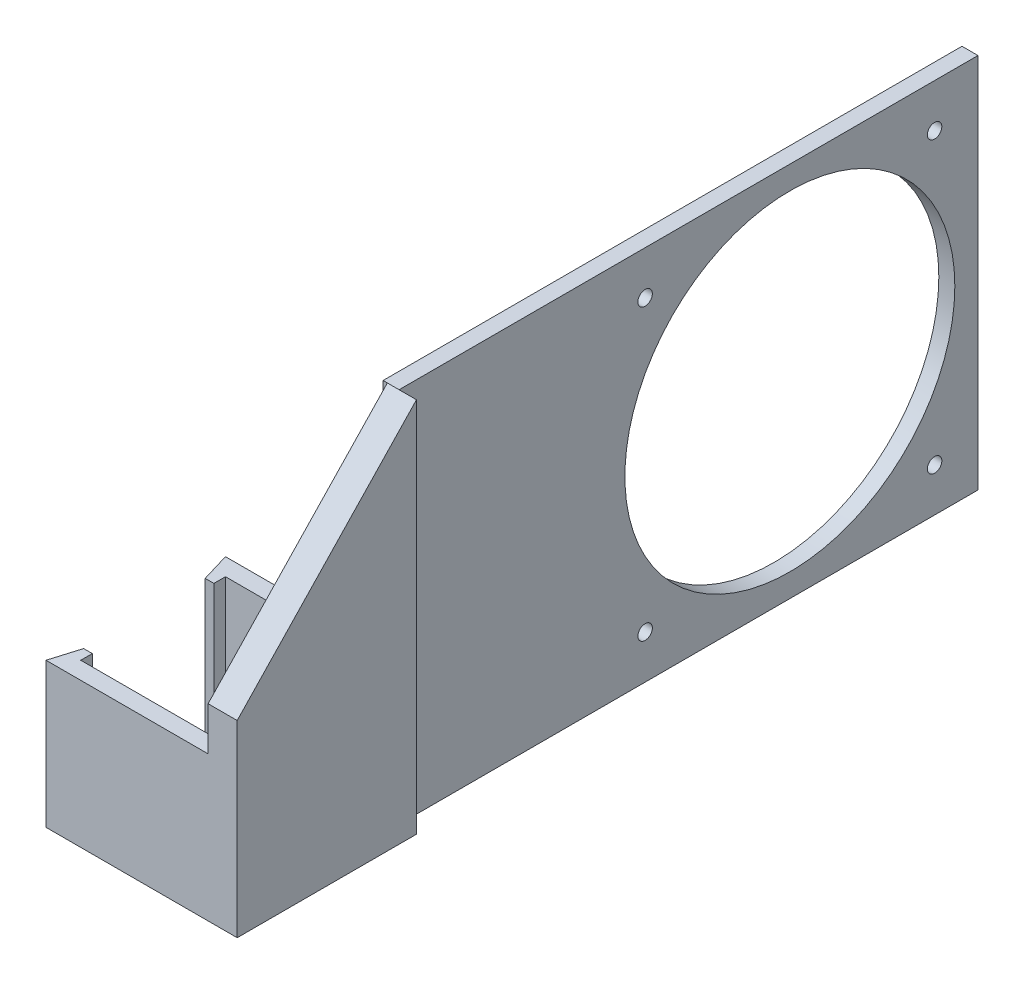
SolidWorks part; units mm, degrees
ref_plane "Спереди" through (0, 0, 0) normal (0, 0, 1) x (1, 0, 0)
ref_plane "Сверху" through (0, 0, 0) normal (0, 1, 0) x (1, 0, 0)
ref_plane "Справа" through (0, 0, 0) normal (1, 0, 0) x (0, 0, -1)
sketch "Эскиз1" plane through (0, 0, 0) normal (0, 1, 0) x (1, 0, 0)
  line L0 (-66.8258, 34.9697) -> (-66.8258, 29.9697)
  line L1 (-63.8258, 29.9697) -> (-63.8258, 31.9697)
  line L2 (-63.8258, 31.9697) -> (-38.8258, 31.9697)
  line L3 (-38.8258, 31.9697) -> (-38.8258, 6.9697)
  line L4 (-38.8258, 6.9697) -> (-63.8258, 6.9697)
  line L5 (-63.8258, 6.9697) -> (-63.8258, 8.9697)
  line L6 (-63.8258, 8.9697) -> (-66.8258, 8.9697)
  line L7 (-66.8258, 8.9697) -> (-66.8258, 3.9697)
  line L8 (-66.8258, 3.9697) -> (-22.1235, 3.9697)
  line L9 (-22.1235, 3.9697) -> (-36.579, 34.9697)
  line L10 (-36.579, 34.9697) -> (-66.8258, 34.9697)
  line L11 (-66.8258, 29.9697) -> (-63.8258, 29.9697)
  dimension "D1" = 25
  dimension "D2" = 25
  dimension "D3" = 25
  dimension "D4" = 155
  dimension "D5" = 3
  dimension "D6" = 3
  dimension "D7" = 3
  dimension "D8" = 3
  dimension "D9" = 2
  dimension "D10" = 2
extrude "Бобышка-Вытянуть1" add sketch "Эскиз1" along normal blind 25
sketch "Эскиз3" plane through (0, 0, 0) normal (0, -1, 0) x (1, 0, 0)
  line L0 (-66.8258, -3.9697) -> (-65.3258, -8.9697)
  line L1 (-63.8258, -8.9697) -> (-66.8258, -8.9697) construction
  line L2 (-65.3258, -8.9697) -> (-66.8258, -8.9697)
  line L3 (-66.8258, -8.9697) -> (-66.8258, -3.9697)
  line L4 (-66.8258, -29.9697) -> (-66.8258, -34.9697)
  line L5 (-66.8258, -34.9697) -> (-65.3258, -29.9697)
  line L6 (-66.8258, -29.9697) -> (-63.8258, -29.9697) construction
  line L7 (-65.3258, -29.9697) -> (-66.8258, -29.9697)
extrude "Вырез-Вытянуть4" cut sketch "Эскиз3" against normal through all
sketch "Эскиз7" plane through (0, 0, 0) normal (0, -1, 0) x (-1, 0, 0)
  line L1 (36.0076, 1.3029) -> (19.3993, 1.3029)
  line L2 (36.0076, 1.3029) -> (36.0076, 39.7765)
  line L3 (36.0076, 39.7765) -> (19.3993, 39.7765)
  line L4 (19.3993, 1.3029) -> (19.3993, 39.7765)
extrude "Вырез-Вытянуть14" cut sketch "Эскиз7" against normal through all
sketch "Эскиз8" plane through (0, 0, 0) normal (0, -1, 0) x (-1, 0, 0)
  line L0 (66.8258, 3.9697) -> (36.0076, 3.9697) construction
  line L1 (38.7989, 3.9697) -> (33.7989, 3.9697)
  line L2 (38.7989, 3.9697) -> (38.7989, 34.9383)
  line L3 (38.7989, 34.9383) -> (33.7989, 34.9383)
  line L4 (33.7989, 3.9697) -> (33.7989, 34.9383)
  dimension "D1" = 5
extrude "Бобышка-Вытянуть2" add sketch "Эскиз8" against normal up to surface (25 mm away) up to face at (-54.2963, 25, -20.5678)
sketch "Эскиз9" plane through (0, 0, -34.9383) normal (0, 0, -1) x (-1, 0, 0)
  line L0 (36.5643, 0) -> (33.7989, 0) construction
  line L1 (36.7989, 0) -> (39.5643, 0)
  line L2 (36.7989, 0) -> (36.7989, 65)
  line L3 (36.7989, 65) -> (39.5643, 65)
  line L4 (39.5643, 0) -> (39.5643, 65)
  line L5 (33.7989, 25) -> (33.7989, 0) construction
  line L6 (36.5643, 25) -> (36.5643, 0) construction
  dimension "D1" = 3
  dimension "D2" = 3
  dimension "D3" = 65
extrude "Бобышка-Вытянуть3" add sketch "Эскиз9" along normal blind 100
sketch "Эскиз10" plane through (0, 25, 0) normal (0, 1, 0) x (1, 0, 0)
  line L0 (-66.8258, 3.9697) -> (-33.7989, 3.9697) construction
  line L1 (-33.7989, 34.9383) -> (-38.8258, 34.9383)
  line L2 (-33.7989, 34.9383) -> (-33.7989, 3.9697)
  line L3 (-33.7989, 3.9697) -> (-38.8258, 3.9697)
  line L4 (-38.8258, 34.9383) -> (-38.8258, 3.9697)
extrude "Бобышка-Вытянуть4" add sketch "Эскиз10" along normal up to surface (40 mm away) up to face at (-38.1816, 65, -84.9383)
sketch "Эскиз11" plane through (-33.7989, 0, 0) normal (1, 0, 0) x (0, 0, -1)
  line L0 (34.9383, 65) -> (3.9697, 32.5) construction
  line L1 (3.9697, 65) -> (3.9697, 0) construction
  line L2 (34.9383, 65) -> (3.9697, 32.5)
  line L3 (3.9697, 32.5) -> (3.9697, 65)
  line L4 (3.9697, 65) -> (34.9383, 65)
extrude "Вырез-Вытянуть15" cut sketch "Эскиз11" against normal blind 100
sketch "Эскиз12" plane through (-36.7989, 0, 0) normal (1, 0, 0) x (0, 0, -1)
  line L0 (69.9383, 65) -> (69.9383, 0) construction
  line L1 (134.9383, 65) -> (34.9383, 65) construction
  line L2 (134.9383, 0) -> (34.9697, 0) construction
  line L3 (134.9383, 65) -> (134.9383, 0) construction
  line L4 (69.9383, 0) -> (134.9383, 65) construction
  circle A0 centre (102.4383, 32.5) radius 28.5
  dimension "D1" = 65
extrude "Вырез-Вытянуть16" cut sketch "Эскиз12" against normal blind 100
sketch "Эскиз13" plane through (-36.7989, 0, 0) normal (1, 0, 0) x (0, 0, -1)
  line L0 (134.9383, 32.5) -> (61.5486, 32.5) construction
  line L1 (134.9383, 65) -> (134.9383, 0) construction
  line L2 (102.4383, 32.5) -> (102.4383, 61) construction
  line L3 (102.4383, 61) -> (102.4383, 4) construction
  line L4 (65.365, 57.5) -> (138.8305, 57.5) construction
  line L5 (127.4383, 65) -> (127.4383, -8.7306) construction
  line L6 (134.9383, 65) -> (34.9383, 65) construction
  line L7 (62.5027, 7.5) -> (133.2422, 7.5) construction
  line L8 (77.4383, 65) -> (77.4383, 0) construction
  line L9 (134.9383, 0) -> (34.9697, 0) construction
  circle A0 centre (102.4383, 32.5) radius 28.5 construction
  circle A1 centre (77.4383, 57.5) radius 1.25
  circle A2 centre (127.4383, 57.5) radius 1.25
  circle A3 centre (127.4383, 7.5) radius 1.25
  circle A4 centre (77.4383, 7.5) radius 1.25
  dimension "D1" = 25
  dimension "D2" = 25
  dimension "D3" = 25
  dimension "D4" = 25
extrude "Вырез-Вытянуть17" cut sketch "Эскиз13" against normal blind 100
chamfer "Фаска1" distance 10 angle 45 1 edges at (-39.5643, 12.5, -34.9697)
